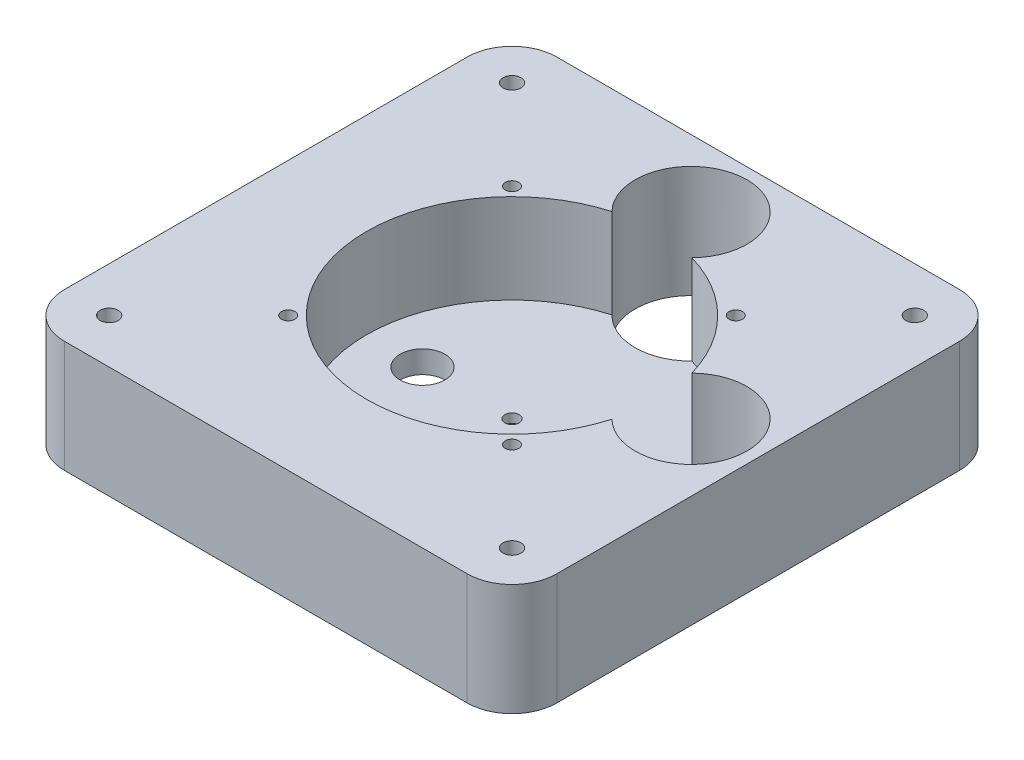
SolidWorks part; units mm, degrees
ref_plane "前视基准面" through (0, 0, 0) normal (0, 0, 1) x (1, 0, 0)
ref_plane "上视基准面" through (0, 0, 0) normal (0, 1, 0) x (1, 0, 0)
ref_plane "右视基准面" through (0, 0, 0) normal (1, 0, 0) x (0, 0, -1)
sketch "草图1" plane through (0, 0, 0) normal (0, 1, 0) x (1, 0, 0)
  line L0 (40, 21.9203) -> (61.9203, 0) construction
  line L1 (-60, 70) -> (70, 70)
  line L2 (-60, 70) -> (-60, -60)
  line L3 (-60, -60) -> (70, -60)
  line L4 (70, 70) -> (70, -60)
  line L5 (61.9203, 0) -> (40, -21.9203) construction
  line L6 (21.9203, 40) -> (0, 61.9203) construction
  line L7 (0, 61.9203) -> (-21.9203, 40) construction
  arc A0 (-8.9268, 31.25) -> (31.25, -8.9268) centre (0, 0) ccw
  arc A1 (31.25, -8.9268) -> (31.25, 8.9268) centre (40, 0) ccw
  arc A2 (8.9268, 31.25) -> (-8.9268, 31.25) centre (0, 40) ccw
  arc A3 (31.25, 8.9268) -> (8.9268, 31.25) centre (0, 0) ccw
  circle A6 centre (61.9203, 0) radius 1.6
  circle A7 centre (40, -21.9203) radius 1.6
  circle A8 centre (40, 21.9203) radius 1.6
  circle A9 centre (21.9203, 40) radius 1.6
  circle A10 centre (-21.9203, 40) radius 1.6
  circle A11 centre (0, 61.9203) radius 1.6
  dimension "D1" = 65
  dimension "D2" = 25
  dimension "D4" = 25
  dimension "D12" = 3.2
  dimension "D3" = 40
  dimension "D5" = 40
  dimension "D6" = 70
  dimension "D7" = 130
  dimension "D8" = 70
  dimension "D9" = 130
  dimension "D10" = 31
  dimension "D11" = 31
  dimension "D13" = 31
  dimension "D14" = 31
extrude "凸台-拉伸1" add sketch "草图1" along normal blind 25
sketch "草图2" plane through (0, 0, 0) normal (0, -1, 0) x (1, 0, 0)
  arc A0 (-8.9268, -31.25) -> (8.9268, -31.25) centre (0, -40) ccw construction
  arc A1 (31.25, 8.9268) -> (-8.9268, -31.25) centre (0, 0) ccw construction
  arc A2 (31.25, -8.9268) -> (31.25, 8.9268) centre (40, 0) ccw construction
  arc A3 (8.9268, -31.25) -> (31.25, -8.9268) centre (0, 0) ccw construction
  arc A4 (-8.9268, -31.25) -> (8.9268, -31.25) centre (0, -40) ccw
  arc A5 (31.25, 8.9268) -> (-8.9268, -31.25) centre (0, 0) ccw
  arc A6 (31.25, -8.9268) -> (31.25, 8.9268) centre (40, 0) ccw
  arc A7 (8.9268, -31.25) -> (31.25, -8.9268) centre (0, 0) ccw
  circle A8 centre (-20, 0) radius 5
  dimension "D2" = 10
  dimension "D1" = 20
extrude "凸台-拉伸2" add sketch "草图2" against normal blind 5
sketch "草图3" plane through (0, 25, 0) normal (0, 1, 0) x (1, 0, 0)
  circle A0 centre (-25, 25) radius 1.5
  circle A1 centre (25, 25) radius 1.5
  circle A2 centre (-25, -25) radius 1.5
  circle A3 centre (25, -25) radius 1.5
  circle A4 centre (-45, 45) radius 2
  circle A5 centre (45, 45) radius 2
  circle A6 centre (45, -45) radius 2
  circle A7 centre (-45, -45) radius 2
  dimension "D5" = 3
  dimension "D10" = 4
  dimension "D1" = 50
  dimension "D2" = 25
  dimension "D3" = 25
  dimension "D4" = 50
  dimension "D6" = 90
  dimension "D7" = 45
  dimension "D8" = 45
  dimension "D9" = 90
extrude "切除-拉伸1" cut sketch "草图3" against normal through all
fillet "圆角1" radius 10 4 edges at (70, 12.5, -70) (-60, 12.5, -70) (70, 12.5, 60) (-60, 12.5, 60)
sketch "草图4" plane through (0, 5, 0) normal (0, 1, 0) x (1, 0, 0)
  circle A0 centre (0, 0) radius 1.6
  dimension "D1" = 3.2
extrude "切除-拉伸2" cut sketch "草图4" against normal blind 10
sketch "草图5" plane through (0, 5, 0) normal (0, 1, 0) x (1, 0, 0)
  circle A0 centre (40, 0) radius 12.5
  circle A1 centre (0, 40) radius 12.5
  dimension "D1" = 25
  dimension "D2" = 25
extrude "切除-拉伸3" cut sketch "草图5" against normal blind 10
sketch "草图6" plane through (0, 25, 0) normal (0, 1, 0) x (1, 0, 0)
  line L1 (45, -55) -> (-45, -55)
  line L2 (55, -45) -> (55, 45)
  line L3 (45, 55) -> (-45, 55)
  line L4 (-55, -45) -> (-55, 45)
  circle A0 centre (-45, 45) radius 2 construction
  circle A1 centre (45, 45) radius 2 construction
  circle A2 centre (-45, -45) radius 2 construction
  arc A3 (45, -55) -> (55, -45) centre (45, -45) ccw
  arc A4 (55, 45) -> (45, 55) centre (45, 45) ccw
  arc A5 (-45, -55) -> (-55, -45) centre (-45, -45) cw
  arc A6 (-45, 55) -> (-55, 45) centre (-45, 45) ccw
  dimension "D1" = 10
  dimension "D2" = 10
  dimension "D3" = 10
  dimension "D4" = 10
  dimension "D5" = 10
extrude "切除-拉伸4" cut sketch "草图6" against normal through all flip side to cut
sketch "草图7" plane through (0, 0, 0) normal (0, -1, 0) x (1, 0, 0)
  circle A0 centre (0, 0) radius 3.5
  dimension "D1" = 7
extrude "切除-拉伸5" cut sketch "草图7" against normal blind 3
sketch "草图9" plane through (0, 0, 0) normal (0, -1, 0) x (1, 0, 0)
  circle A0 centre (-21.9203, -40) radius 3.5
  circle A1 centre (21.9203, -40) radius 3.5
  circle A2 centre (40, -21.9203) radius 3.5
  circle A3 centre (40, 21.9203) radius 3.5
  circle A4 centre (-47, 25) radius 3.5
  circle A5 centre (-47, -25) radius 3.5
  dimension "D1" = 7
extrude "切除-拉伸6" cut sketch "草图9" against normal blind 5
sketch "草图10" plane through (0, 25, 0) normal (0, 1, 0) x (1, 0, 0)
  circle A0 centre (40, 21.9203) radius 1.6 construction
  circle A1 centre (40, -21.9203) radius 1.6 construction
  circle A2 centre (-21.9203, 40) radius 1.6 construction
  circle A3 centre (21.9203, 40) radius 1.6 construction
  circle A4 centre (40, 21.9203) radius 1.6
  circle A5 centre (40, -21.9203) radius 1.6
  circle A6 centre (-21.9203, 40) radius 1.6
  circle A7 centre (21.9203, 40) radius 1.6
extrude "凸台-拉伸3" add sketch "草图10" against normal up to surface (20 mm away) up to face at (40, 5, -23.5203)
sketch "草图11" plane through (0, 0, 0) normal (0, -1, 0) x (1, 0, 0)
  circle A0 centre (25, 25) radius 1.5 construction
  circle A1 centre (-25, 25) radius 1.5 construction
  circle A2 centre (-25, -25) radius 1.5 construction
  circle A3 centre (25, -25) radius 1.5 construction
  circle A4 centre (25, 25) radius 1.5
  circle A5 centre (-25, 25) radius 1.5
  circle A6 centre (-25, -25) radius 1.5
  circle A7 centre (25, -25) radius 1.5
extrude "凸台-拉伸4" add sketch "草图11" against normal blind 13
